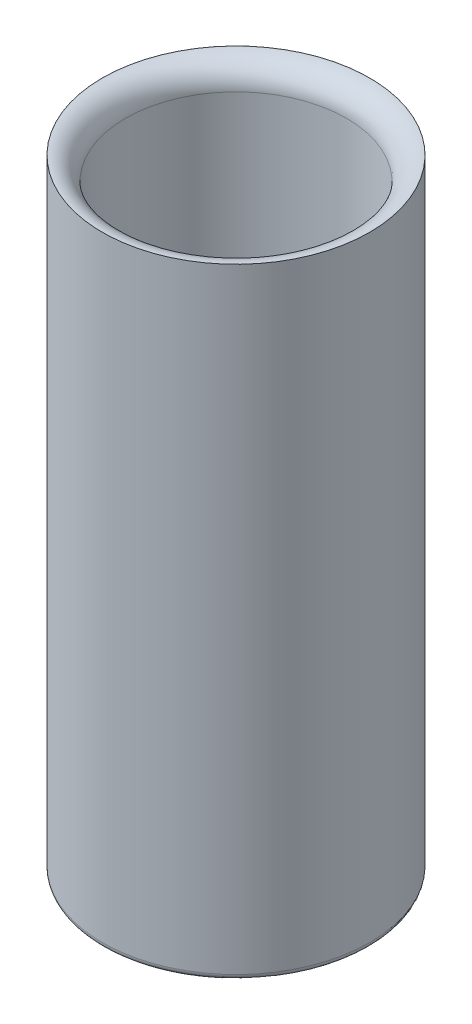
SolidWorks part; units mm, degrees
ref_plane "Płaszczyzna przednia" through (0, 0, 0) normal (0, 0, 1) x (1, 0, 0)
ref_plane "Płaszczyzna górna" through (0, 0, 0) normal (0, 1, 0) x (1, 0, 0)
ref_plane "Płaszczyzna prawa" through (0, 0, 0) normal (1, 0, 0) x (0, 0, -1)
sketch "Szkic1" plane through (0, 0, 0) normal (0, 0, 1) x (1, 0, 0)
  line L0 (0, -51.8535) -> (0, 61.6013) construction
  line L1 (0, -51.8535) -> (-22.04, -51.8535)
  line L2 (-23.04, -50.8535) -> (-23.04, 55.1465)
  line L3 (0, -42.8935) -> (0, -51.8535)
  line L5 (-19.02, -41.1451) -> (-19.02, 51.1465)
  line L6 (-23.02, 55.1465) -> (-23.04, 55.1465)
  line L7 (-22.04, -51.8535) -> (-22.04, 50.5465) construction
  line L8 (-22.04, 50.5465) -> (-19.02, 50.5465) construction
  line L10 (-9.51, -42.8935) -> (-18.1072, -42.1413)
  line L11 (-9.51, -42.8935) -> (0, -42.8935)
  line L12 (-9.51, -42.8935) -> (0, -42.8935)
  arc A0 (-19.02, -41.1451) -> (-18.1072, -42.1413) centre (-18.02, -41.1451) ccw
  arc A1 (-19.02, 51.1465) -> (-23.02, 55.1465) centre (-23.02, 51.1465) ccw
  arc A3 (-23.04, -50.8535) -> (-22.04, -51.8535) centre (-22.04, -50.8535) ccw
  dimension "D1" = 1
  dimension "D6" = 4
  dimension "D2" = 8.96
  dimension "D3" = 19.02
  dimension "D4" = 23.04
  dimension "D5" = 107
  dimension "D7" = 102.4
  dimension "D8" = 9.51
revolve "Obrót1" add sketch "Szkic1" angle 360 about L0
